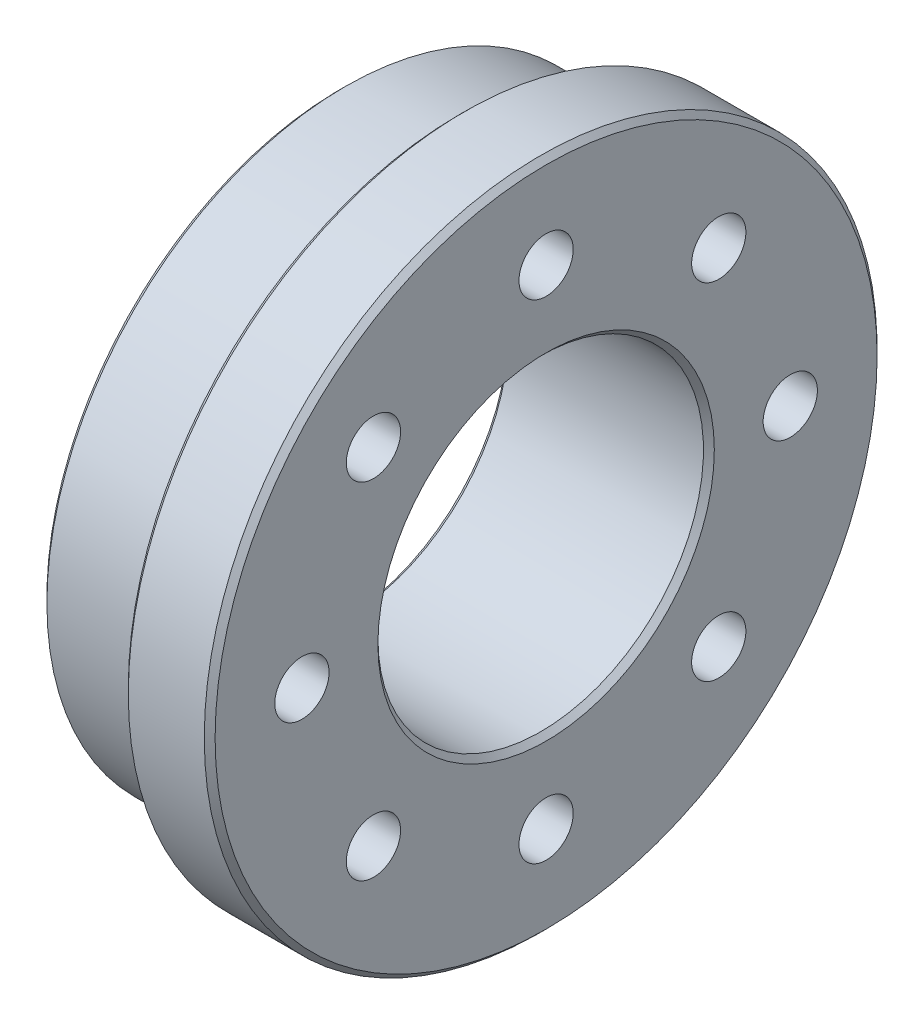
SolidWorks part; units mm, degrees
ref_plane "前视基准面" through (0, 0, 0) normal (0, 0, 1) x (1, 0, 0)
ref_plane "上视基准面" through (0, 0, 0) normal (0, 1, 0) x (1, 0, 0)
ref_plane "右视基准面" through (0, 0, 0) normal (1, 0, 0) x (0, 0, -1)
other "Configuration Table"
sketch "草图1" plane through (0, 0, 0) normal (0, 0, 1) x (1, 0, 0)
  line L0 (0, 0) -> (137.0092, 0) construction
  line L1 (0, 15) -> (19, 15)
  line L2 (19, 15) -> (19, 31)
  line L3 (19, 31) -> (11, 31)
  line L4 (11, 31) -> (11, 27.5)
  line L5 (11, 27.5) -> (0, 27.5)
  line L6 (0, 27.5) -> (0, 15)
  dimension "D1" = 30
  dimension "D2" = 19
  dimension "D3" = 11
  dimension "D4" = 55
  dimension "D5" = 62
revolve "旋转1" add sketch "草图1" angle 360 about L0
sketch "草图2" plane through (19, 0, 0) normal (1, 0, 0) x (0, 0, -1)
  circle A0 centre (0, 0) radius 22.5 construction
  circle A1 centre (0, 22.5) radius 2.5
  circle A2 centre (15.9099, 15.9099) radius 2.5
  circle A3 centre (22.5, 0) radius 2.5
  circle A4 centre (15.9099, -15.9099) radius 2.5
  circle A5 centre (0, -22.5) radius 2.5
  circle A6 centre (-15.9099, -15.9099) radius 2.5
  circle A7 centre (-22.5, 0) radius 2.5
  circle A8 centre (-15.9099, 15.9099) radius 2.5
  point P5 (0, 0)
  point P6 (22.5, 0)
  point P22 (0, 0)
  dimension "D1" = 45
  dimension "D2" = 5
  dimension "D3" = 8
extrude "切除-拉伸1" cut sketch "草图2" against normal blind 15
chamfer "倒角1" distance 0.5 angle 45 5 edges at (19, 0, 31) (11, 0, 31) (0, 0, 27.5) (0, 0, 15) (19, 0, 15)
